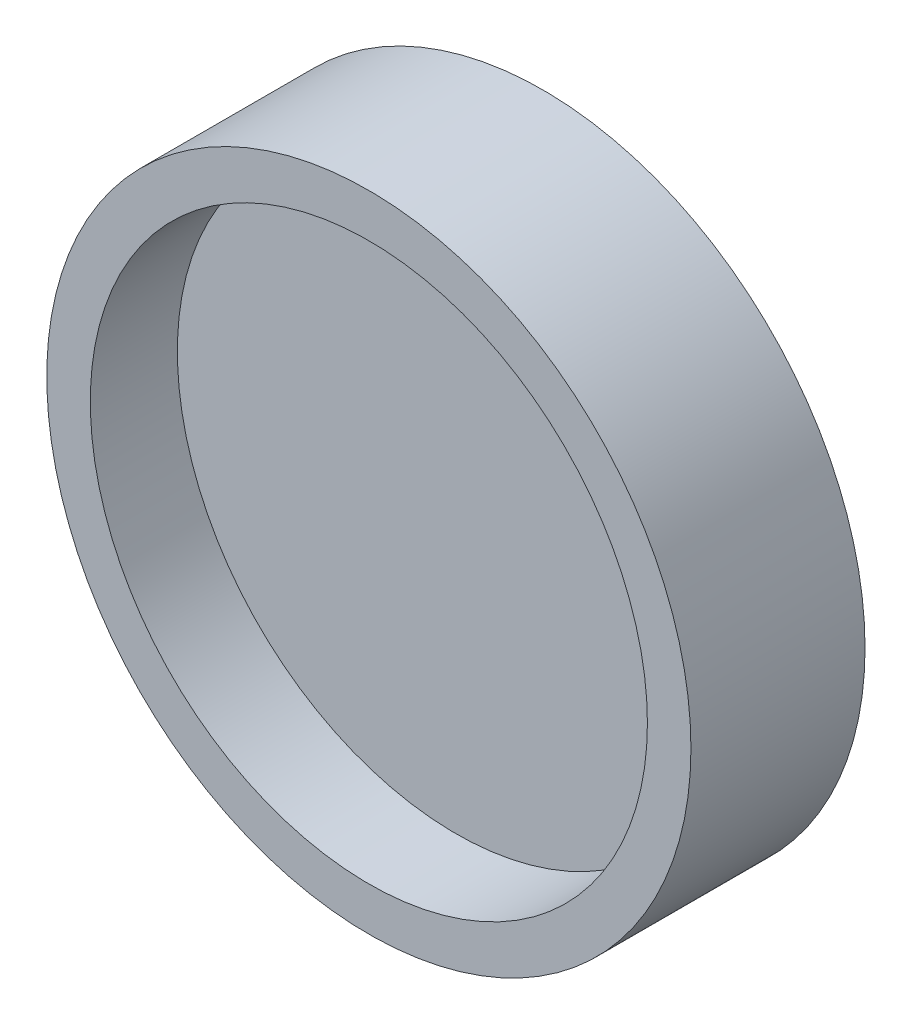
SolidWorks part; units mm, degrees
ref_plane "Front Plane" through (0, 0, 0) normal (0, 0, 1) x (1, 0, 0)
ref_plane "Top Plane" through (0, 0, 0) normal (0, 1, 0) x (1, 0, 0)
ref_plane "Right Plane" through (0, 0, 0) normal (1, 0, 0) x (0, 0, -1)
sketch "Sketch1" plane through (0, 0, 0) normal (0, 0, 1) x (1, 0, 0)
  circle A1 centre (0, 0) radius 74
  point P1 (0, 0)
  dimension "D2" = 148
extrude "Boss-Extrude1" add sketch "Sketch1" along normal blind 40
sketch "Sketch2" plane through (0, 0, 40) normal (0, 0, 1) x (1, 0, 0)
  circle A0 centre (0, 0) radius 64
  dimension "D1" = 128
extrude "Cut-Extrude1" cut sketch "Sketch2" against normal blind 20
